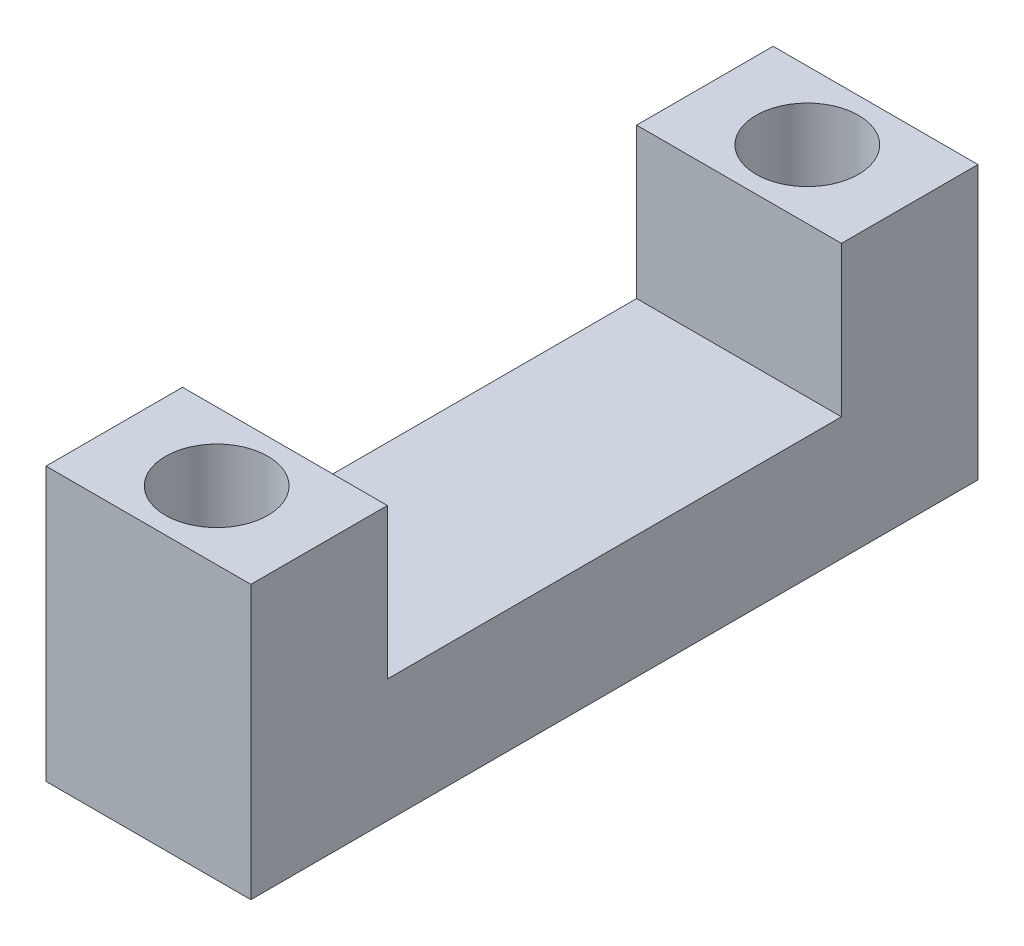
SolidWorks part; units mm, degrees
material "AISI 类型 A2 刀具钢"
ref_plane "前视基准面" through (0, 0, 0) normal (0, 0, 1) x (1, 0, 0)
ref_plane "上视基准面" through (0, 0, 0) normal (0, 1, 0) x (1, 0, 0)
ref_plane "右视基准面" through (0, 0, 0) normal (1, 0, 0) x (0, 0, -1)
sketch "草图1" plane through (0, 0, 0) normal (1, 0, 0) x (0, 0, -1)
  line L0 (0, 0) -> (0, 8)
  line L1 (0, 8) -> (4, 8)
  line L2 (4, 8) -> (4, 3.6)
  line L3 (4, 3.6) -> (17.3, 3.6)
  line L4 (17.3, 3.6) -> (17.3, 8)
  line L5 (17.3, 8) -> (21.3, 8)
  line L6 (21.3, 8) -> (21.3, 0)
  line L7 (21.3, 0) -> (0, 0)
  line L8 (10.65, 0) -> (10.65, 3.6) construction
  dimension "D1" = 13.3
  dimension "D2" = 4.4
  dimension "D3" = 4
  dimension "D4" = 3.6
extrude "凸台-拉伸1" add sketch "草图1" along normal blind 6
sketch "草图2" plane through (0, 8, 0) normal (0, 1, 0) x (1, 0, 0)
  line L0 (3, 0) -> (3, 21.3) construction
  line L3 (6, 0) -> (0, 0) construction
  line L4 (6, 21.3) -> (0, 21.3) construction
  point P6 (3, 19.3)
  point P7 (3, 2)
  dimension "D2" = 2
  dimension "D1" = 2
hole_wizard "大小mm Clearance 暗销孔1" positions "3D草图1" profile "草图3" hole size "Ø3.0" standard "GB" end condition through all
sketch3d "3D草图1"
  point P0 (3, 8, -2)
  point P4 (3, 8, -19.3)
sketch "草图3" plane through (3, 8, -2) normal (1, 0, 0) x (0, 0, 1)
  line L0 (0, 0) -> (0, 8)
  line L1 (0, 8) -> (1.5, 8)
  line L2 (1.5, 8) -> (1.5, 0)
  line L5 (1.5, 0) -> (0, 0)
  line L11 (0, -6.35) -> (0, 107.95) construction
  dimension "通孔孔直径" = 3
  dimension "通孔孔深度" = 8
